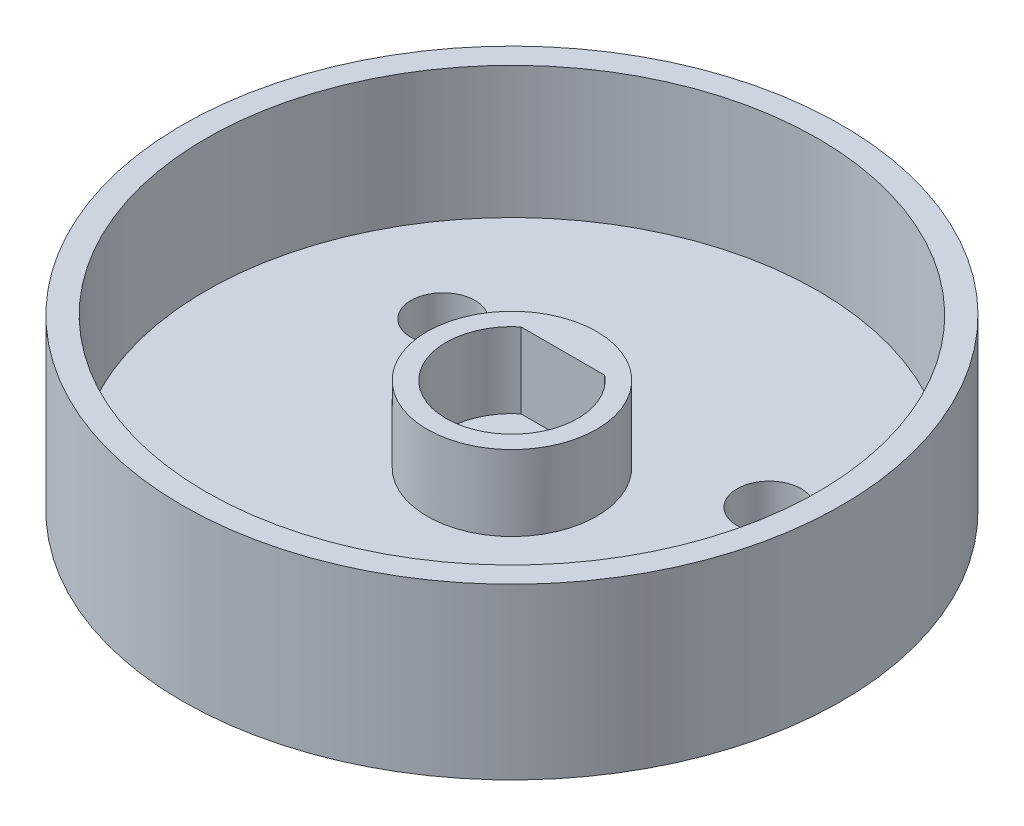
SolidWorks part; units mm, degrees
ref_plane "Front Plane" through (0, 0, 0) normal (1, 0, 0) x (0, 1, 0)
ref_plane "Top Plane" through (0, 0, 0) normal (0, 0, 1) x (0, 1, 0)
ref_plane "Right Plane" through (0, 0, 0) normal (0, 1, 0) x (-1, 0, 0)
sketch "Sketch1" plane through (0, 0, 0) normal (1, 0, 0) x (0, 1, 0)
  line L0 (-60, -45) -> (-60, 45)
  line L1 (60, -45) -> (-60, -45) construction
  line L2 (60, -45) -> (60, 45) construction
  line L3 (60, 45) -> (-60, 45) construction
  line L4 (-60, -45) -> (-60, 45) construction
  line L5 (60, -45) -> (-60, 45) construction
  line L6 (60, 45) -> (-60, -45) construction
  line L7 (-60, 45) -> (60, 45)
  line L8 (60, 45) -> (60, -45)
  line L9 (60, -45) -> (56, -45)
  line L10 (56, -45) -> (56, 41)
  line L11 (56, 41) -> (-56, 41)
  line L12 (-56, 41) -> (-56, -45)
  line L13 (-56, -45) -> (-60, -45)
  point P0 (0, 0)
  dimension "D1" = 120
  dimension "D2" = 90
  dimension "D3" = 4
  dimension "D4" = 4
extrude "Boss-Extrude1" add sketch "Sketch1" along normal blind 150
sketch "Sketch2" plane through (0, 60, 0) normal (0, 1, 0) x (-1, 0, 0)
  circle A0 centre (-105.5397, 0.1293) radius 35
  circle A3 centre (-105.5397, 0.1293) radius 32.5
  dimension "D1" = 70
  dimension "D5" = 65
extrude "Boss-Extrude2" add sketch "Sketch2" along normal blind 14 contours A3 | A0
sketch "Sketch3" plane through (0, 60, 0) normal (0, 1, 0) x (-1, 0, 0)
  line L0 (-109.9897, -5.2742) -> (-101.0897, -5.2742)
  arc A1 (-101.0897, -5.2742) -> (-109.9897, -5.2742) centre (-105.5397, 0.1293) ccw
  circle A2 centre (-105.5397, 0.1293) radius 9
  dimension "D1" = 18
  dimension "D2" = 14
  dimension "D3" = 8.9
extrude "Boss-Extrude3" add sketch "Sketch3" along normal blind 8
sketch "Sketch5" plane through (0, 60, 0) normal (0, 1, 0) x (-1, 0, 0)
  circle A0 centre (-105.5397, 0.1293) radius 3.4
  dimension "D1" = 6.8
extrude "Cut-Extrude1" cut sketch "Sketch5" against normal blind 14
sketch "Sketch8" plane through (150, 0, 0) normal (1, 0, 0) x (0, 1, 0)
  line L0 (60, 35.1293) -> (56, 35.1293)
  line L1 (-60, 45) -> (56, 45)
  line L2 (-60, 45) -> (-60, -45)
  line L3 (-60, -45) -> (56, -45)
  line L4 (56, 35.1293) -> (56, -34.8707)
  line L5 (56, 45) -> (60, 45)
  line L6 (60, 45) -> (60, 35.1293)
  line L7 (60, -45) -> (60, -34.8707)
  line L8 (60, -34.8707) -> (56, -34.8707)
  line L9 (60, -45) -> (56, -45)
extrude "Cut-Extrude4" cut sketch "Sketch8" against normal blind 154
sketch "Sketch11" plane through (0, 60, 0) normal (0, 1, 0) x (-1, 0, 0)
  line L1 (-150, 35.1293) -> (-105.5397, 35.1293)
  line L2 (-150, 35.1293) -> (-150, -34.8707)
  line L3 (-150, -34.8707) -> (-105.5397, -34.8707)
  arc A0 (-105.5397, 35.1293) -> (-105.5397, -34.8707) centre (-105.5397, 0.1293) ccw
  arc A1 (-105.5397, 35.1293) -> (-105.5397, -34.8707) centre (-105.5397, 0.1293) ccw construction
extrude "Cut-Extrude6" cut sketch "Sketch11" against normal blind 4
sketch "Sketch12" plane through (0, 60, 0) normal (0, 1, 0) x (-1, 0, 0)
  line L0 (-105.5397, 35.1293) -> (0, 35.1293)
  line L1 (0, 35.1293) -> (0, -34.8707)
  line L2 (0, -34.8707) -> (-105.5397, -34.8707)
  arc A0 (-105.5397, 35.1293) -> (-105.5397, -34.8707) centre (-105.5397, 0.1293) cw
  circle A1 centre (-105.5397, 0.1293) radius 35 construction
extrude "Cut-Extrude7" cut sketch "Sketch12" against normal blind 4
sketch "Sketch13" plane through (0, 56, 0) normal (0, -1, 0) x (1, 0, 0)
  line L0 (105.5397, 0.1293) -> (105.5397, 20.1293) construction
  circle A0 centre (105.5397, 20.1293) radius 3.4
  dimension "D1" = 6.8
  dimension "D2" = 20
extrude "Cut-Extrude8" cut sketch "Sketch13" against normal blind 10
pattern_circular "CirPattern1" count 3 every 120 about axis through (105.5397, 0, 0.1293) along (0, 1, 0) of "Cut-Extrude8"
